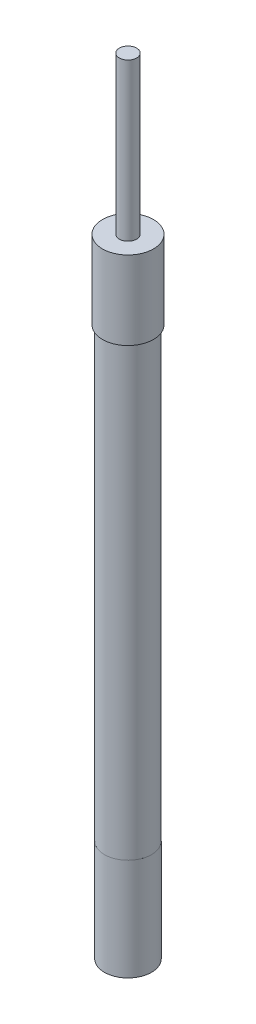
SolidWorks part; units mm, degrees
ref_plane "Front Plane" through (0, 0, 0) normal (0, 0, 1) x (1, 0, 0)
ref_plane "Top Plane" through (0, 0, 0) normal (0, 1, 0) x (1, 0, 0)
ref_plane "Right Plane" through (0, 0, 0) normal (1, 0, 0) x (0, 0, -1)
sketch "SK Bulb guard" plane through (0, 0, 0) normal (0, 1, 0) x (1, 0, 0)
  circle A0 centre (0, 0) radius 6
extrude "Bulb guard" add sketch "SK Bulb guard" along normal blind 26 separate body
sketch "SK Electrode body" plane through (0, 0, 0) normal (0, 1, 0) x (1, 0, 0)
  circle A0 centre (0, 0) radius 6
extrude "Electrode body" add sketch "SK Electrode body" along normal blind 114 from offset 26 separate body
sketch "SK Electrode cap" plane through (0, 0, 0) normal (0, 1, 0) x (1, 0, 0)
  circle A0 centre (0, 0) radius 6.5
extrude "Electrode cap" add sketch "SK Electrode cap" along normal blind 20 from offset 140 separate body
sketch "SK Cable" plane through (0, 0, 0) normal (0, 1, 0) x (1, 0, 0)
  circle A0 centre (0, 0) radius 2.2
extrude "Cable" add sketch "SK Cable" along normal blind 40 from offset 160 separate body
